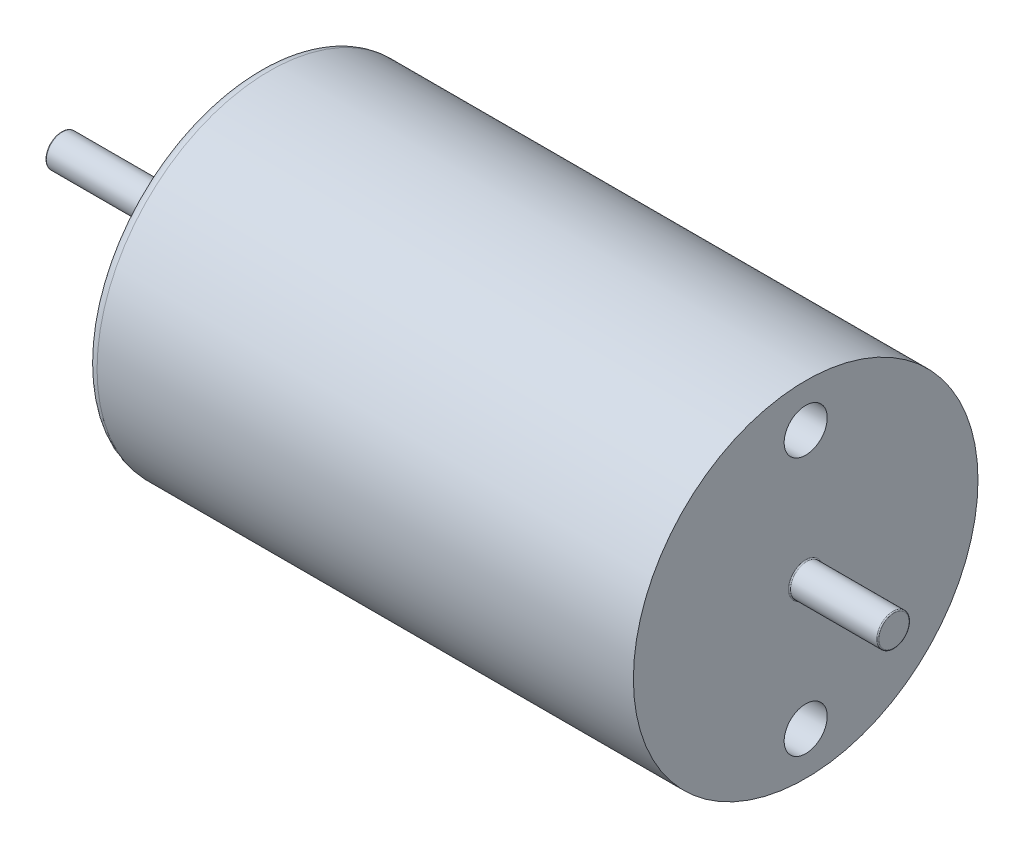
SolidWorks part; units mm, degrees
ref_plane "Front Plane" through (0, 0, 0) normal (0, 0, 1) x (1, 0, 0)
ref_plane "Top Plane" through (0, 0, 0) normal (0, 1, 0) x (1, 0, 0)
ref_plane "Right Plane" through (0, 0, 0) normal (1, 0, 0) x (0, 0, -1)
sketch "Sketch1" plane through (0, 0, 0) normal (0, 1, 0) x (1, 0, 0)
  line L0 (0, 0) -> (-38.65, 0)
  line L1 (-38.65, 0) -> (-38.65, 0.75)
  line L4 (-29.5, 8) -> (-4.1, 8)
  line L11 (-32.3, 0.75) -> (-32.3, 2.5)
  line L12 (-32.3, 2.5) -> (-29.5, 2.5)
  line L15 (-38.65, 0.75) -> (-32.3, 0.75)
  line L16 (-29.5, 2.5) -> (-29.5, 8)
  line L17 (-4.1, 8) -> (-4.1, 0.75)
  line L19 (-4.1, 0.75) -> (0, 0.75)
  line L20 (0, 0.75) -> (0, 0)
  dimension "D1" = 0.75
  dimension "16" = 8
  dimension "D2" = 25.4
  dimension "D3" = 9.15
  dimension "D4" = 2.8
  dimension "D5" = 2.5
  dimension "D6" = 0.75
  dimension "D7" = 4.1
revolve "Revolve1" add sketch "Sketch1" angle 360 about L0
sketch "Sketch2" plane through (-29.5, 0, 0) normal (-1, 0, 0) x (0, 0, 1)
  line L0 (0, 0) -> (0, 5) construction
  circle A1 centre (0, 5) radius 1
  dimension "D1" = 2
  dimension "D2" = 5
extrude "Cut-Extrude2" cut sketch "Sketch2" against normal blind 3 contours A1
pattern_circular "CirPattern1" count 6 every 60 about axis through (0, 0, 0) along (1, 0, 0) of "Cut-Extrude2"
fillet "Fillet2" radius 0.5 1 edges at (-29.5, 0, -8)
fillet "Fillet3" radius 0.05 6 edges at (-29.5, 0, -2.5) (0, 0, -0.75) (-4.1, 0, -0.75) (-38.65, 0, -0.75) (-32.3, 0, -0.75) (-32.3, 0, -2.5)
sketch "Sketch3" plane through (-4.1, 0, 0) normal (1, 0, 0) x (0, 0, -1)
  line L0 (0, 0) -> (0, 6) construction
  circle A0 centre (0, 6) radius 1
  dimension "D2" = 2
  dimension "D1" = 6
extrude "Cut-Extrude3" cut sketch "Sketch3" against normal blind 3
pattern_circular "CirPattern2" count 2 every 180 about axis through (0, 0, 0) along (1, 0, 0) of "Cut-Extrude3"
